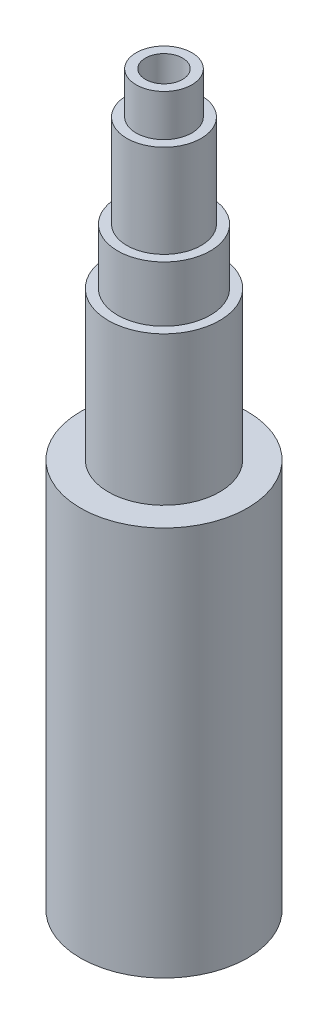
SolidWorks part; units mm, degrees
material "Plain Carbon Steel"
ref_plane "Front Plane" through (0, 0, 0) normal (0, 0, 1) x (1, 0, 0)
ref_plane "Top Plane" through (0, 0, 0) normal (0, 1, 0) x (1, 0, 0)
ref_plane "Right Plane" through (0, 0, 0) normal (1, 0, 0) x (0, 0, -1)
sketch "Sketch1" plane through (0, 0, 0) normal (0, 1, 0) x (1, 0, 0)
  circle A0 centre (0, 0) radius 9
  dimension "D1" = 18
extrude "base section" add sketch "Sketch1" along normal blind 42
sketch "Sketch2" plane through (0, 42, 0) normal (0, 1, 0) x (1, 0, 0)
  circle A0 centre (0, 0) radius 6
  dimension "D1" = 12
extrude "second section" add sketch "Sketch2" along normal blind 16
sketch "Sketch3" plane through (0, 58, 0) normal (0, 1, 0) x (1, 0, 0)
  circle A0 centre (0, 0) radius 5
  dimension "D1" = 10
extrude "bearing section" add sketch "Sketch3" along normal blind 6
sketch "Sketch4" plane through (0, 64, 0) normal (0, 1, 0) x (1, 0, 0)
  circle A0 centre (0, 0) radius 4
  dimension "D1" = 8
extrude "seal section" add sketch "Sketch4" along normal blind 10
sketch "Sketch5" plane through (0, 74, 0) normal (0, 1, 0) x (1, 0, 0)
  circle A0 centre (0, 0) radius 3
  dimension "D1" = 6
extrude "impeller section" add sketch "Sketch5" along normal blind 4.5
sketch "Sketch6" plane through (0, 78.5, 0) normal (0, 1, 0) x (1, 0, 0)
  circle A0 centre (0, 0) radius 2
  dimension "D1" = 4
extrude "impeller screw hole" cut sketch "Sketch6" against normal blind 10
sketch "Sketch7" plane through (0, 0, 0) normal (0, -1, 0) x (-1, 0, 0)
  circle A0 centre (0, 0) radius 4
  dimension "D1" = 8
extrude "motor shaft hole" cut sketch "Sketch7" against normal blind 32
equation "\"D1@Sketch1\"=\"coupler shaft base diameter\""
equation "\"bearing OD\" = 20mm"
equation "\"bearing outer race thickness\"= 1mm"
equation "\"bearing ID\"= 10mm"
equation "\"bearing depth\"= 6mm"
equation "\"bearing inner race thickness\"= 1mm"
equation "\"seal OD\" = 20mm"
equation "\"seal ID\"= 8mm"
equation "\"seal depth\"= 6mm"
equation "\"impeller base outer diameter\"= 1.75in"
equation "\"impeller base outer thickness\"= 1mm"
equation "\"impeller base center thickness\"= 5mm"
equation "\"impeller number of vanes\"= 8"
equation "\"impeller vane inner height\"= 8mm"
equation "\"impeller primary vane opening diamater\"= 10mm"
equation "\"impeller vane inner thickness\"= .75mm"
equation "\"impeller vane outer thickness\"= 1.5mm"
equation "\"impeller primary vane entrance angle\"= 20deg"
equation "\"impeller secondary vane entrance angle\"= 20deg"
equation "\"impeller secondary vane opening diameter\"= 10mm"
equation "\"motor to housing distance\"= 60mm"
equation "\"motor mount pattern diameter\"= 30mm"
equation "\"motor mount coupler shaft hole diameter\"= \"coupler shaft base diameter\"+ 4mm"
equation "\"motor mount to housing m8 screw hole diameter\"= 8.5mm"
equation "\"motor mount to housing m8 screw post radius\"= ( 3 * \"motor mount to housing m8 screw hole diameter\" ) / 2"
equation "\"motor mount to housing m8 pattern diameter\"= 100mm"
equation "\"motor mount to housing m4 screw hole diamater\"= 4mm"
equation "\"motor mount to housing m4 head diameter\"= 7.25mm"
equation "\"motor mount to housing m4 head depth\"= 4mm"
equation "\"motor mount plate thickness\"= 6mm + \"motor mount to housing m4 head depth\""
equation "\"motor shaft pride\"= 32mm"
equation "\"motor shaft flat section length from tip\"= 25.7mm"
equation "\"motor shaft bore end clearance\"= 2mm"
equation "\"motor mount shaft hole depth\"= \"motor shaft pride\""
equation "\"coupler shaft set screw drill hole diameter\"= 6mm"
equation "\"coupler shaft motor shaft hole diameter\"= 8mm"
equation "\"coupler shaft base diameter\"= 18mm"
equation "\"coupler shaft base length\"= \"motor mount shaft hole depth\" + 10mm"
equation "\"coupler shaft second section diameter\"= \"bearing ID\" + \"bearing inner race thickness\" * 2"
equation "\"coupler shaft third section diamater\"= \"bearing ID\""
equation "\"coupler shaft second section length\"= \"motor to housing distance\" -  \"coupler shaft base length\" - 2mm"
equation "\"coupler shaft set screw 1 distance\"= \"motor mount shaft hole depth\" / 3"
equation "\"coupler shaft set screw 2 distance\"= \"motor mount shaft hole depth\" * 4 / 5"
equation "\"housing bearing seat lip thickness\" = 2mm"
equation "\"housing base thickness\"= \"housing bearing seat lip thickness\" + \"seal depth\" + \"bearing depth\""
equation "\"housing top impeller vertical clearance\"= 1mm"
equation "\"housing top impeller horizontal clearance\"= 1mm"
equation "\"housing top impeller bottom clearance\"= 2mm"
equation "\"housing top impeller cavity height\"= \"housing top impeller bottom clearance\" + \"impeller base center thickness\" + \"impeller vane inner height\" + \"housing top impeller vertical clearance\""
equation "\"housing top impeller cavity diameter\"= 2 * \"housing top impeller horizontal clearance\" + \"impeller base outer diameter\""
equation "\"housing top impeller cavity tip height\"= \"housing top impeller bottom clearance\" + \"housing top impeller vertical clearance\" + \"impeller base outer thickness\" + \"impeller vane outer height\""
equation "\"housing top entrance OD\"= 20mm"
equation "\"housing top exit OD\"= 5mm"
equation "\"housing top o-ring channel height\"= 1.5mm"
equation "\"housing top o ring channel width\"= 1.5mm"
equation "\"housing top threaded inlet depth\"= 8mm"
equation "\"housing top total thickness\"= \"housing top threaded inlet depth\" + \"housing top impeller cavity height\""
equation "\"housing top total width\"= 10mm"
equation "\"housing top exit threaded diameter\"= 8mm"
equation "\"housing top exit threaded depth\"= 8mm"
equation "\"coupler shaft third section length\"= \"bearing depth\""
equation "\"coupler shaft seal section diameter\" = \"seal ID\""
equation "\"coupler shaft seal section length\" = \"housing base thickness\"+\"housing top impeller bottom clearance\"-\"bearing depth\""
equation "\"coupler shaft impeller section diameter\" = 6mm"
equation "\"coupler shaft impeller section length\" = \"impeller bolt surface height\"-.5mm"
equation "\"D1@base section\" = \"coupler shaft base length\""
equation "\"D1@Sketch2\"=\"coupler shaft second section diameter\""
equation "\"D1@second section\" = \"coupler shaft second section length\""
equation "\"D1@Sketch3\"=\"coupler shaft third section diamater\""
equation "\"D1@bearing section\" = \"coupler shaft third section length\""
equation "\"D1@Sketch4\"=\"coupler shaft seal section diameter\""
equation "\"D1@seal section\" = \"coupler shaft seal section length\""
equation "\"D1@Sketch5\"=\"coupler shaft impeller section diameter\""
equation "\"D1@impeller section\" = \"coupler shaft impeller section length\""
equation "\"coupler shaft impeller screw hole diameter\" = \"motor mount to housing m4 screw hole diamater\""
equation "\"coupler shaft impeller screw hole depth\" = 10mm"
equation "\"D1@Sketch6\"=\"coupler shaft impeller screw hole diameter\""
equation "\"D1@impeller screw hole\" = \"coupler shaft impeller screw hole depth\""
equation "\"D1@Sketch7\"=\"coupler shaft motor shaft hole diameter\""
equation "\"D1@motor shaft hole\" = \"motor mount shaft hole depth\""
equation "\"impeller vane outer height\"= 4mm"
equation "\"impeller bolt surface height\" = 5mm"
equation "\"impeller bolt surface diameter\" = 8mm"
equation "\"housing top o-ring circumference\" = 250mm"
equation "\"housing top o-ring radius\" = (\"housing top o-ring circumference\")/(2*3.14)"
equation "\"coupler shaft to motor clearance\" = 2mm"
